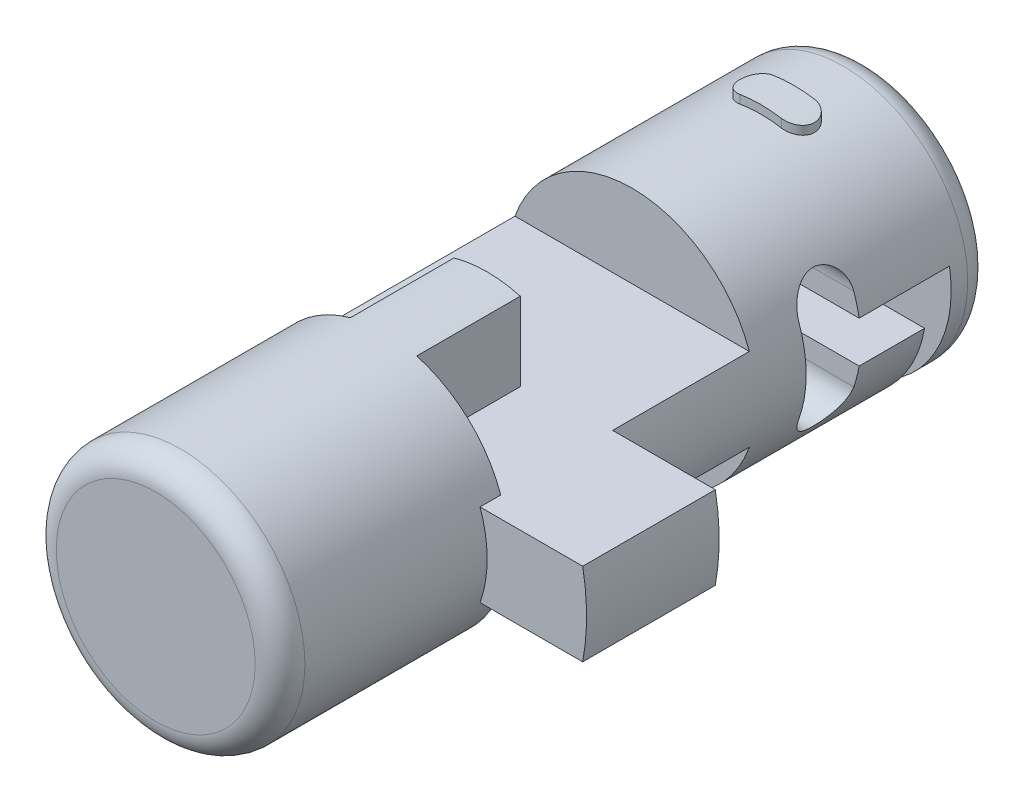
SolidWorks part; units mm, degrees
material "Nylon 101"
ref_plane "Front Plane" through (0, 0, 0) normal (0, 0, 1) x (1, 0, 0)
ref_plane "Top Plane" through (0, 0, 0) normal (0, 1, 0) x (1, 0, 0)
ref_plane "Right Plane" through (0, 0, 0) normal (1, 0, 0) x (0, 0, -1)
sketch "Sketch1" plane through (0, 0, 0) normal (0, 0, 1) x (1, 0, 0)
  circle A0 centre (0, 0) radius 3.81
  dimension "D1" = 7.62
extrude "Boss-Extrude1" add sketch "Sketch1" along normal mid plane 21.844
ref_plane "Plane1" through (0, 3.81, 0) normal (0, 1, 0) x (1, 0, 0)
ref_plane "Plane2" through (0, 1.27, 0) normal (0, 1, 0) x (1, 0, 0)
sketch "Sketch2" plane through (0, 1.27, 0) normal (0, 1, 0) x (1, 0, 0)
  line L0 (-3.81, 10.922) -> (-3.81, -10.922) construction
  line L1 (-3.81, 3.683) -> (3.81, 3.683)
  line L2 (-3.81, 3.683) -> (-3.81, -3.937)
  line L3 (-3.81, -3.937) -> (-1.016, -3.937)
  line L4 (3.81, 3.683) -> (3.81, -3.937)
  line L5 (-3.81, 3.683) -> (3.81, -3.937) construction
  line L6 (-3.81, -3.937) -> (3.81, 3.683) construction
  line L7 (3.81, -10.922) -> (3.81, 10.922) construction
  line L8 (-3.81, -10.922) -> (3.81, -10.922) construction
  line L9 (1.016, -3.937) -> (3.81, -3.937)
  line L11 (-1.016, -3.937) -> (-1.016, -0.762)
  line L12 (-1.016, -0.762) -> (1.016, -0.762)
  line L13 (1.016, -3.937) -> (1.016, -0.762)
  line L14 (-1.016, -3.937) -> (1.016, -0.762) construction
  line L15 (-1.016, -0.762) -> (1.016, -3.937) construction
  point P4 (0, -0.127)
  point P15 (0, -2.3495)
  dimension "D1" = 6.985
  dimension "D2" = 7.62
  dimension "D3" = 3.175
  dimension "D4" = 2.032
  dimension "D5" = 1.016
extrude "Cut-Extrude1" cut sketch "Sketch2" along normal through all
mirror "Mirror1" about plane through (0, 0, 0) normal (0, 1, 0) of "Cut-Extrude1"
sketch "Sketch3" plane through (0, 0, 0) normal (1, 0, 0) x (0, 0, -1)
  line L0 (6.0458, -1.27) -> (6.0458, 1.27) construction
  line L1 (5.207, -1.27) -> (5.207, 1.27)
  line L2 (6.8847, -1.27) -> (6.8847, -0.635)
  line L3 (6.8847, 0.635) -> (9.652, 0.635)
  line L4 (9.652, 0.635) -> (9.652, -3.81)
  line L5 (3.683, -3.81) -> (10.922, -3.81) construction
  line L6 (9.652, -3.81) -> (8.89, -3.81)
  line L7 (8.89, -3.81) -> (8.89, -0.635)
  line L8 (8.89, -0.635) -> (6.8847, -0.635)
  line L9 (-10.922, 0) -> (10.922, 0) construction
  line L10 (10.922, -3.81) -> (10.922, 3.81) construction
  line L11 (6.8847, 0.635) -> (6.8847, 1.27)
  arc A0 (5.207, -1.27) -> (6.8847, -1.27) centre (6.0458, -1.27) ccw
  arc A1 (6.8847, 1.27) -> (5.207, 1.27) centre (6.0458, 1.27) ccw
  point P2 (6.0458, 0)
  dimension "D1" = 2.54
  dimension "D2" = 1.524
  dimension "D3" = 1.27
  dimension "D4" = 0.635
  dimension "D5" = 1.27
  dimension "D6" = 0.762
  dimension "D7" = 1.6777
extrude "Cut-Extrude2" cut sketch "Sketch3" against normal mid plane 21.844 contours A1 L1 A0 L2 L8 L7 L6 L4 L3 L11
sketch "Sketch4" plane through (0, 0, 0) normal (1, 0, 0) x (0, 0, -1)
  line L0 (-3.937, 1.27) -> (3.683, 1.27) construction
  line L1 (-0.508, 1.27) -> (-4.572, 1.27)
  line L2 (-0.508, 1.27) -> (-0.508, -1.27)
  line L3 (-0.508, -1.27) -> (-4.572, -1.27)
  line L4 (-4.572, 1.27) -> (-4.572, -1.27)
  line L5 (-0.508, 1.27) -> (-4.572, -1.27) construction
  line L6 (-0.508, -1.27) -> (-4.572, 1.27) construction
  line L9 (3.683, -1.27) -> (-3.937, -1.27) construction
  line L10 (-10.922, 3.81) -> (-10.922, -3.81) construction
  point P4 (-2.54, 0)
  dimension "D1" = 4.064
  dimension "D2" = 6.35
extrude "Boss-Extrude2" add sketch "Sketch4" along normal offset from surface (6.7394 mm away) 3.048
sketch "Sketch5" plane through (0, 0.635, 0) normal (0, 1, 0) x (1, 0, 0)
  line L0 (-0.635, 8.128) -> (0.635, 8.128) construction
  line L1 (-0.635, 8.636) -> (0.635, 8.636)
  line L2 (-0.635, 7.62) -> (0.635, 7.62)
  line L3 (3.81, 10.922) -> (-3.81, 10.922) construction
  arc A0 (-0.635, 8.636) -> (-0.635, 7.62) centre (-0.635, 8.128) ccw
  arc A1 (0.635, 7.62) -> (0.635, 8.636) centre (0.635, 8.128) ccw
  point P2 (0, 8.128)
  dimension "D2" = 0.508
  dimension "D1" = 1.27
  dimension "D3" = 2.286
extrude "Boss-Extrude3" add sketch "Sketch5" along normal offset from surface (3.3791 mm away) 0.254
mirror "Mirror2" about plane through (0, 0, 0) normal (0, 1, 0) of "Boss-Extrude3"
fillet "Fillet1" radius 0.762 2 edges at (3.81, 0, -10.922) (3.81, 0, 10.922)
